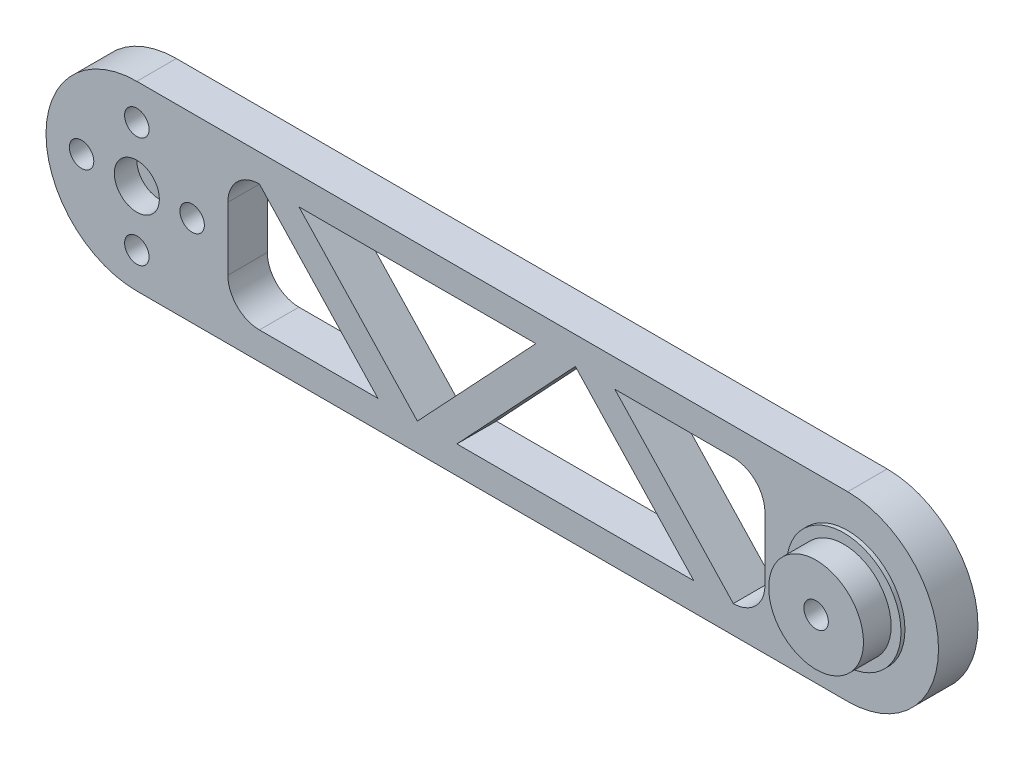
SolidWorks part; units mm, degrees
ref_plane "前视基准面" through (0, 0, 0) normal (0, 0, 1) x (1, 0, 0)
ref_plane "上视基准面" through (0, 0, 0) normal (0, 1, 0) x (1, 0, 0)
ref_plane "右视基准面" through (0, 0, 0) normal (1, 0, 0) x (0, 0, -1)
other "Configuration Table"
sketch "Sketch2" plane through (0, 0, 0) normal (0, 0, 1) x (1, 0, 0)
  line L0 (0, 0) -> (90, 0) construction
  line L1 (0, 11.5) -> (90, 11.5)
  line L2 (0, -11.5) -> (90, -11.5)
  arc A0 (0, 11.5) -> (0, -11.5) centre (0, 0) ccw
  arc A1 (90, -11.5) -> (90, 11.5) centre (90, 0) ccw
  circle A2 centre (90, 0) radius 6
  point P3 (45, 0)
extrude "Boss-Extrude1" add sketch "Sketch2" against normal blind 5 contours L1 A1 L2 A0
sketch "Sketch11" plane through (0, 0, 0) normal (0, 0, 1) x (1, 0, 0)
  circle A0 centre (90, 0) radius 7.25
extrude "Boss-Extrude3" add sketch "Sketch11" along normal blind 0.5 contours A0
sketch "Sketch12" plane through (0, 0, 0.5) normal (0, 0, 1) x (1, 0, 0)
  circle A0 centre (90, 0) radius 6
extrude "Boss-Extrude4" add sketch "Sketch12" along normal blind 3.5 contours A0
sketch "Sketch13" plane through (0, 0, 4) normal (0, 0, 1) x (1, 0, 0)
  circle A0 centre (90, 0) radius 1.55
extrude "Cut-Extrude1" cut sketch "Sketch13" against normal blind 20.5
sketch "Sketch14" plane through (0, 0, -5) normal (0, 0, -1) x (-1, 0, 0)
  line L1 (-93.2136, -0.3551) -> (-91.2993, -2.9606)
  line L2 (-91.2993, -2.9606) -> (-88.0857, -2.6055)
  line L3 (-88.0857, -2.6055) -> (-86.7864, 0.3551)
  line L4 (-86.7864, 0.3551) -> (-88.7007, 2.9606)
  line L5 (-88.7007, 2.9606) -> (-91.9143, 2.6055)
  line L6 (-91.9143, 2.6055) -> (-93.2136, -0.3551)
  circle A0 centre (-90, 0) radius 2.8 construction
extrude "Cut-Extrude2" cut sketch "Sketch14" against normal blind 2.6 contours L4 L5 L6 L1 L2 L3
sketch "Sketch17" plane through (0, 0, 0) normal (0, 0, 1) x (1, 0, 0)
  circle A0 centre (0, 7) radius 1.55
  circle A1 centre (0, -7) radius 1.55
  circle A2 centre (-7, 0) radius 1.55
  circle A3 centre (7, 0) radius 1.55
  dimension "D1" = 14
  dimension "D2" = 14
  dimension "D3" = 7
  dimension "D4" = 7
extrude "Cut-Extrude4" cut sketch "Sketch17" against normal blind 10.02 contours A3 | A1 | A2 | A0
sketch "Sketch18" plane through (0, 0, 0) normal (0, 0, 1) x (1, 0, 0)
  circle A0 centre (0, 0) radius 2.85
extrude "Cut-Extrude5" cut sketch "Sketch18" against normal blind 2.85
sketch "Sketch19" plane through (0, 0, 0) normal (0, 0, 1) x (1, 0, 0)
  line L0 (0, 11.5) -> (90, 11.5) construction
  line L1 (15.5215, 8) -> (75.5215, 8)
  line L2 (11.5215, 4) -> (11.5215, -4)
  line L3 (15.5215, -8) -> (75.5215, -8)
  line L4 (79.5215, 4) -> (79.5215, -4)
  line L5 (0, -11.5) -> (90, -11.5) construction
  line L6 (15.5215, 8) -> (20.5215, 8)
  line L7 (15.5215, 8) -> (30.5215, -8)
  line L8 (20.5215, 8) -> (35.5215, -8)
  line L9 (30.5215, -8) -> (35.5215, -8)
  line L10 (35.5215, -8) -> (50.5215, 8)
  line L11 (35.5215, -8) -> (40.5215, -8)
  line L12 (50.5215, 8) -> (55.5215, 8)
  line L13 (40.5215, -8) -> (55.5215, 8)
  line L14 (55.5215, 8) -> (60.5215, 8)
  line L15 (55.5215, 8) -> (70.5215, -8)
  line L16 (60.5215, 8) -> (75.5215, -8)
  line L17 (70.5215, -8) -> (75.5215, -8)
  arc A0 (11.5215, -4) -> (15.5215, -8) centre (15.5215, -4) ccw
  arc A1 (15.5215, 8) -> (11.5215, 4) centre (15.5215, 4) ccw
  arc A2 (75.5215, -8) -> (79.5215, -4) centre (75.5215, -4) ccw
  arc A3 (75.5215, 8) -> (79.5215, 4) centre (75.5215, 4) cw
  point P16 (0, 0)
  point P24 (0, 0)
  point P26 (75.2034, -8)
  point P27 (0, 0)
  point P28 (0, 0)
  point P29 (0, 0)
  point P30 (0, 0)
  point P31 (0, 0)
  point P32 (22.1589, -15.0316)
  point P33 (0, 0)
  dimension "D1" = 4
  dimension "D2" = 3.5
  dimension "D3" = 3.5
  dimension "D4" = 5
  dimension "D5" = 5
  dimension "D6" = 5
  dimension "D7" = 60
  dimension "D8" = 20
  dimension "D9" = 20
extrude "Cut-Extrude7" cut sketch "Sketch19" against normal blind 10 contours L7 A1 L2 A0 L3 | L8 L10 L1 | L15 L13 L3 | A3 L1 L16 A2 L4
